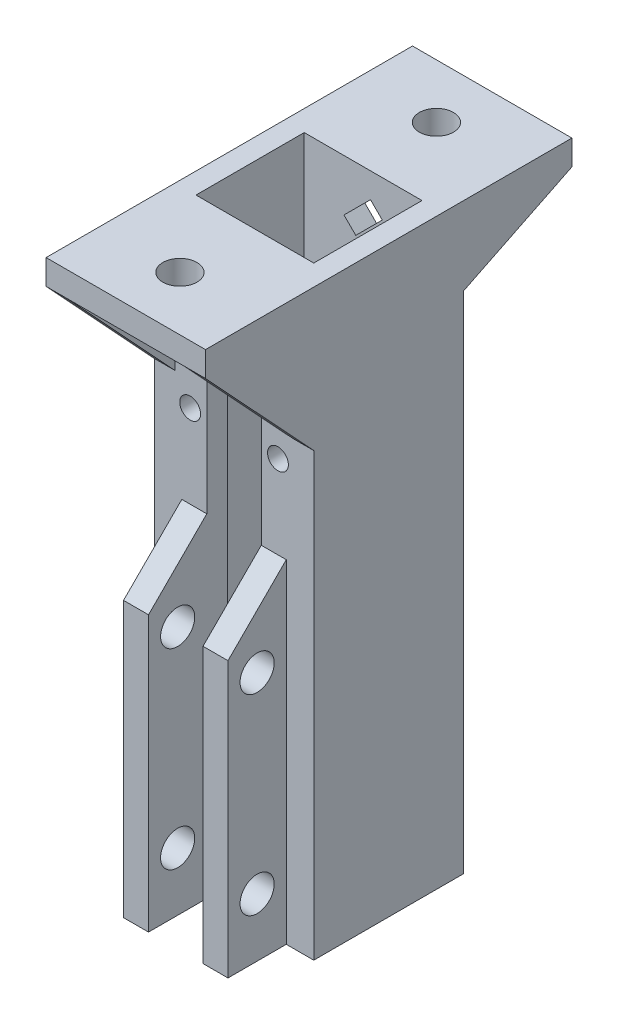
SolidWorks part; units mm, degrees
ref_plane "Front Plane" through (0, 0, 0) normal (0, 0, 1) x (1, 0, 0)
ref_plane "Top Plane" through (0, 0, 0) normal (0, 1, 0) x (1, 0, 0)
ref_plane "Right Plane" through (0, 0, 0) normal (1, 0, 0) x (0, 0, -1)
sketch "Sketch2" plane through (0, 0, 0) normal (0, 1, 0) x (1, 0, 0)
  line L0 (-14.0765, 2.3428) -> (5.0666, 2.3428)
  line L1 (-14.0765, 2.3428) -> (-14.0765, -0.1572)
  line L2 (5.0666, 2.3428) -> (5.0666, -0.1572)
  line L3 (-14.0765, -0.1572) -> (5.0666, -0.1572)
  line L4 (5.0666, 2.3428) -> (5.0666, -13.1572)
  line L5 (5.0666, 2.3428) -> (2.5666, 2.3428)
  line L6 (5.0666, -13.1572) -> (2.5666, -13.1572)
  line L7 (2.5666, 2.3428) -> (2.5666, -13.1572)
  line L8 (-14.0765, 2.3428) -> (-14.0765, -13.1572)
  line L9 (-14.0765, 2.3428) -> (-11.5765, 2.3428)
  line L10 (-14.0765, -13.1572) -> (-11.5765, -13.1572)
  line L11 (-11.5765, 2.3428) -> (-11.5765, -13.1572)
  line L12 (-14.0765, -13.1572) -> (-7.7765, -13.1572)
  line L13 (-14.0765, -13.1572) -> (-14.0765, -15.6572)
  line L14 (-7.7765, -13.1572) -> (-7.7765, -15.6572)
  line L15 (-14.0765, -15.6572) -> (-7.7765, -15.6572)
  line L16 (5.0666, -13.1572) -> (-1.2334, -13.1572)
  line L17 (5.0666, -13.1572) -> (5.0666, -15.6572)
  line L18 (-1.2334, -13.1572) -> (-1.2334, -15.6572)
  line L19 (5.0666, -15.6572) -> (-1.2334, -15.6572)
  line L20 (-7.7765, -15.6572) -> (-10.7765, -15.6572)
  line L21 (-7.7765, -15.6572) -> (-7.7765, -22.6572)
  line L22 (-10.7765, -15.6572) -> (-10.7765, -22.6572)
  line L23 (-7.7765, -22.6572) -> (-10.7765, -22.6572)
  line L24 (-1.2334, -15.6572) -> (1.7666, -15.6572)
  line L25 (-1.2334, -15.6572) -> (-1.2334, -22.6572)
  line L26 (1.7666, -15.6572) -> (1.7666, -22.6572)
  line L27 (-1.2334, -22.6572) -> (1.7666, -22.6572)
  point P0 (-7.9314, -0.1572)
  point P21 (2.5666, -0.1572)
  point P24 (2.5666, -13.1572)
  point P25 (-12.9001, -13.1572)
  dimension "D1" = 0
  dimension "D2" = 2.5
  dimension "D3" = 2.5
  dimension "D4" = 2.5
  dimension "D5" = 6.5431
  dimension "D6" = 360
  dimension "D7" = 13
  dimension "D8" = 2.5
  dimension "D9" = 2.5
  dimension "D10" = 13
  dimension "D11" = 3
  dimension "D12" = 3
  dimension "D13" = 90
  dimension "D14" = 6.3
  dimension "D15" = 6.3
  dimension "D16" = 14.1431
  dimension "D17" = 90
  dimension "D18" = 6.5431
  dimension "D19" = 7
  dimension "D20" = 7
extrude "Boss-Extrude1" add sketch "Sketch2" along normal blind 40 contours L16 L4 L2 L3 L7 | L9 L11 L3 L7 L5 L0 | L8 L12 L11 L3 L1 | L5 L7 L3 L2 | L11 L9 L1 L3 | L13 L15 L14 L12 L11 L10 | L12 L10 L11 | L6 L16 L7 | L19 L17 L6 L7 L16 L18 | L25 L27 L26 L19 | L23 L21 L15 L22
sketch "Sketch3" plane through (-10.7765, 0, 0) normal (-1, 0, 0) x (0, 0, 1)
  line L0 (22.6572, 40) -> (22.6572, 0) construction
  line L1 (15.6572, 40) -> (15.6572, 0) construction
  line L2 (15.6572, 40) -> (22.6572, 40) construction
  line L3 (15.6572, 0) -> (22.6572, 0) construction
  circle A0 centre (19.1572, 30) radius 2.05
  circle A1 centre (19.1572, 7) radius 2.05
  dimension "D5" = 4.1
  dimension "D6" = 4.1
  dimension "D1" = 3.5
  dimension "D2" = 3.5
  dimension "D3" = 3.5
  dimension "D4" = 3.5
  dimension "D7" = 10
  dimension "D8" = 7
extrude "Cut-Extrude2" cut sketch "Sketch3" against normal blind 40
sketch "Sketch26" plane through (0, 40, 0) normal (0, 1, 0) x (1, 0, 0)
  line L0 (1.7666, -15.6572) -> (5.0666, -15.6572)
  line L1 (5.0666, -15.6572) -> (5.0666, 2.3428)
  line L2 (5.0666, 2.3428) -> (-14.0765, 2.3428)
  line L3 (-14.0765, 2.3428) -> (-14.0765, -15.6572)
  line L4 (-14.0765, -15.6572) -> (-7.7765, -15.6572)
  line L5 (-7.7765, -13.1572) -> (-7.7765, -22.6572) construction
  line L6 (-7.7765, -15.6572) -> (-7.7765, -13.1572)
  line L7 (-7.7765, -13.1572) -> (-11.5765, -13.1572)
  line L8 (-11.5765, -13.1572) -> (-11.5765, -0.1572)
  line L9 (-11.5765, -0.1572) -> (2.5666, -0.1572)
  line L10 (2.5666, -0.1572) -> (2.5666, -13.1572)
  line L11 (2.5666, -13.1572) -> (-1.2334, -13.1572)
  line L12 (-1.2334, -13.1572) -> (-1.2334, -15.6572)
  line L13 (-1.2334, -13.1572) -> (-1.2334, -22.6572) construction
  line L14 (-1.2334, -15.6572) -> (1.7666, -15.6572)
  line L15 (1.7666, -15.6572) -> (3.6413, -15.6092)
extrude "Boss-Extrude11" add sketch "Sketch26" along normal blind 30
sketch "Sketch16" plane through (0, 0, 15.6572) normal (0, 0, 1) x (1, 0, 0)
  line L0 (-7.7765, 70) -> (-7.7765, 40) construction
  line L2 (-14.0765, 70) -> (-7.7765, 70) construction
  circle A0 centre (-9.7765, 50) radius 1.25
  dimension "D1" = 20
  dimension "D2" = 2.5
  dimension "D4" = 2
extrude "Cut-Extrude9" cut sketch "Sketch16" along direction (0, 0, 1) on the side against the normal blind 3.5
sketch "Sketch17" plane through (0, 0, 15.6572) normal (0, 0, 1) x (1, 0, 0)
  line L0 (-1.2334, 70) -> (-1.2334, 40) construction
  line L2 (-1.2334, 70) -> (5.0666, 70) construction
  circle A0 centre (0.7666, 50) radius 1.25
  dimension "D1" = 2.5
  dimension "D2" = 2
  dimension "D3" = 20
extrude "Cut-Extrude10" cut sketch "Sketch17" along direction (0, 0, 1) on the side against the normal blind 3.5
sketch "Sketch18" plane through (0, 0, 13.1572) normal (0, 0, -1) x (-1, 0, 0)
  line L1 (-5.0666, 70) -> (14.0765, 70)
  line L2 (-5.0666, 70) -> (-5.0666, 67)
  line L3 (-5.0666, 67) -> (14.0765, 67)
  line L4 (14.0765, 70) -> (14.0765, 67)
  line L6 (-5.0666, 70) -> (-5.0666, 0) construction
  line L8 (14.0765, 70) -> (7.7765, 70) construction
  dimension "D1" = 0
  dimension "D2" = 0
  dimension "D3" = 3
  dimension "D4" = 0
extrude "Boss-Extrude4" add sketch "Sketch18" against normal blind 15.5
sketch "Sketch19" plane through (0, 0, -2.3428) normal (0, 0, -1) x (-1, 0, 0)
  line L0 (-5.0666, 70) -> (-5.0666, 0) construction
  line L1 (14.0765, 70) -> (-5.0666, 70)
  line L2 (14.0765, 70) -> (14.0765, 67)
  line L3 (14.0765, 67) -> (-5.0666, 67)
  line L4 (-5.0666, 70) -> (-5.0666, 67)
  line L5 (14.0765, 70) -> (14.0765, 0) construction
  dimension "D1" = 3
  dimension "D2" = 0
extrude "Boss-Extrude5" add sketch "Sketch19" along normal blind 13 and the other way blind 2 contours L1 L4 L3 L2
sketch "Sketch21" plane through (-14.0765, 0, 0) normal (-1, 0, 0) x (0, 0, 1)
  line L0 (28.6572, 67) -> (15.6572, 53)
  line L1 (15.6572, 67) -> (15.6572, 0) construction
  line L2 (15.6572, 53) -> (15.6572, 67)
  line L3 (15.6572, 67) -> (28.6572, 67)
  dimension "D1" = 14
extrude "Boss-Extrude6" add sketch "Sketch21" against normal blind 2.5
sketch "Sketch22" plane through (5.0666, 0, 0) normal (1, 0, 0) x (0, 0, -1)
  line L0 (-28.6572, 67) -> (-15.6572, 67)
  line L1 (-15.6572, 67) -> (-15.6572, 53)
  line L2 (-15.6572, 67) -> (-15.6572, 0) construction
  line L3 (-15.6572, 53) -> (-28.6572, 67)
  dimension "D1" = 14
extrude "Boss-Extrude8" add sketch "Sketch22" against normal blind 2.5
sketch "Sketch23" plane through (5.0666, 0, 0) normal (1, 0, 0) x (0, 0, -1)
  line L0 (-13.1572, 70) -> (-13.1572, 53)
  line L2 (15.3428, 70) -> (15.3428, 67)
  line L3 (15.3428, 70) -> (-13.1572, 70)
  line L4 (15.3428, 67) -> (-13.1572, 53)
  dimension "D1" = 28.5
  dimension "D2" = 28.5
  dimension "D3" = 17
  dimension "D4" = 3
  dimension "D5" = 90
extrude "Boss-Extrude9" add sketch "Sketch23" against normal blind 2.5
sketch "Sketch24" plane through (-14.0765, 0, 0) normal (-1, 0, 0) x (0, 0, 1)
  line L0 (13.1572, 70) -> (-15.3428, 70)
  line L1 (-15.3428, 70) -> (-15.3428, 67)
  line L2 (-15.3428, 67) -> (13.1572, 53)
  line L4 (13.1572, 53) -> (13.1572, 70)
  line L5 (-15.3428, 70) -> (-15.3428, 67) construction
  dimension "D1" = 17
  dimension "D2" = 28.5
  dimension "D3" = 3
  dimension "D4" = 90
  dimension "D5" = 0
extrude "Boss-Extrude10" add sketch "Sketch24" against normal blind 2.5
sketch "Sketch25" plane through (0, 70, 0) normal (0, 1, 0) x (1, 0, 0)
  line L0 (-11.5765, 15.3428) -> (-11.5765, 2.3428) construction
  circle A0 centre (-4.705, 8.8428) radius 2.05
  circle A1 centre (-4.505, -22.1572) radius 2.05
  dimension "D1" = 4.1
  dimension "D2" = 4.1
  dimension "D7" = 6.8715
extrude "Cut-Extrude12" cut sketch "Sketch25" against normal blind 3.5
sketch "Sketch27" plane through (0, 67, 0) normal (0, -1, 0) x (1, 0, 0)
  line L1 (-1.2334, 13.1572) -> (-7.7765, 13.1572)
  line L2 (-1.2334, 13.1572) -> (-1.2334, 15.6572)
  line L3 (-1.2334, 15.6572) -> (-7.7765, 15.6572)
  line L4 (-7.7765, 13.1572) -> (-7.7765, 15.6572)
extrude "Boss-Extrude12" add sketch "Sketch27" along normal blind 12
fillet "Fillet1" radius 1 2 edges at (-7.7765, 55, 14.4072) (-1.2334, 55, 14.4072)
sketch "Sketch28" plane through (0, 0, 15.6572) normal (0, 0, 1) x (1, 0, 0)
  line L0 (-3.621, 66.9965) -> (-6.803, 63.8145)
  line L1 (-3.621, 66.9965) -> (-2.2068, 65.5823)
  line L2 (-6.803, 63.8145) -> (-5.3888, 62.4003)
  line L3 (-2.2068, 65.5823) -> (-5.3888, 62.4003)
  line L4 (-1.2334, 54) -> (-1.2334, 40) construction
  line L5 (-7.7765, 54) -> (-7.7765, 40) construction
  line L7 (-2.2068, 65.5823) -> (-6.803, 63.8145) construction
  line L8 (-5.3888, 62.4003) -> (-3.621, 66.9965) construction
  line L11 (-3.621, 63.4965) -> (-6.803, 60.3145)
  line L12 (-6.803, 60.3145) -> (-5.3888, 58.9003)
  line L13 (-2.2068, 62.0823) -> (-5.3888, 58.9003)
  line L14 (-3.621, 63.4965) -> (-2.2068, 62.0823)
  line L15 (-3.621, 59.9965) -> (-6.803, 56.8145)
  line L16 (-6.803, 56.8145) -> (-5.3888, 55.4003)
  line L17 (-2.2068, 58.5823) -> (-5.3888, 55.4003)
  line L18 (-3.621, 59.9965) -> (-2.2068, 58.5823)
  point P0 (-4.5049, 64.6984)
  dimension "D1" = 2
  dimension "D2" = 4.5
  dimension "D3" = 2
  dimension "D4" = 4.5
  dimension "D5" = 3.2715
  dimension "D6" = 3.2716
  dimension "D7" = 3
  dimension "D9" = 90
  dimension "D10" = 90
extrude "Cut-Extrude13" cut sketch "Sketch28" against normal through all
sketch "Sketch29" plane through (1.7666, 0, 0) normal (1, 0, 0) x (0, 0, -1)
  line L0 (-15.6572, 40) -> (-22.6572, 40)
  line L1 (-22.6572, 40) -> (-22.6572, 33)
  line L2 (-22.6572, 40) -> (-22.6572, 0) construction
  line L3 (-22.6572, 33) -> (-15.6572, 40)
  dimension "D1" = 45
extrude "Cut-Extrude14" cut sketch "Sketch29" against normal through all
